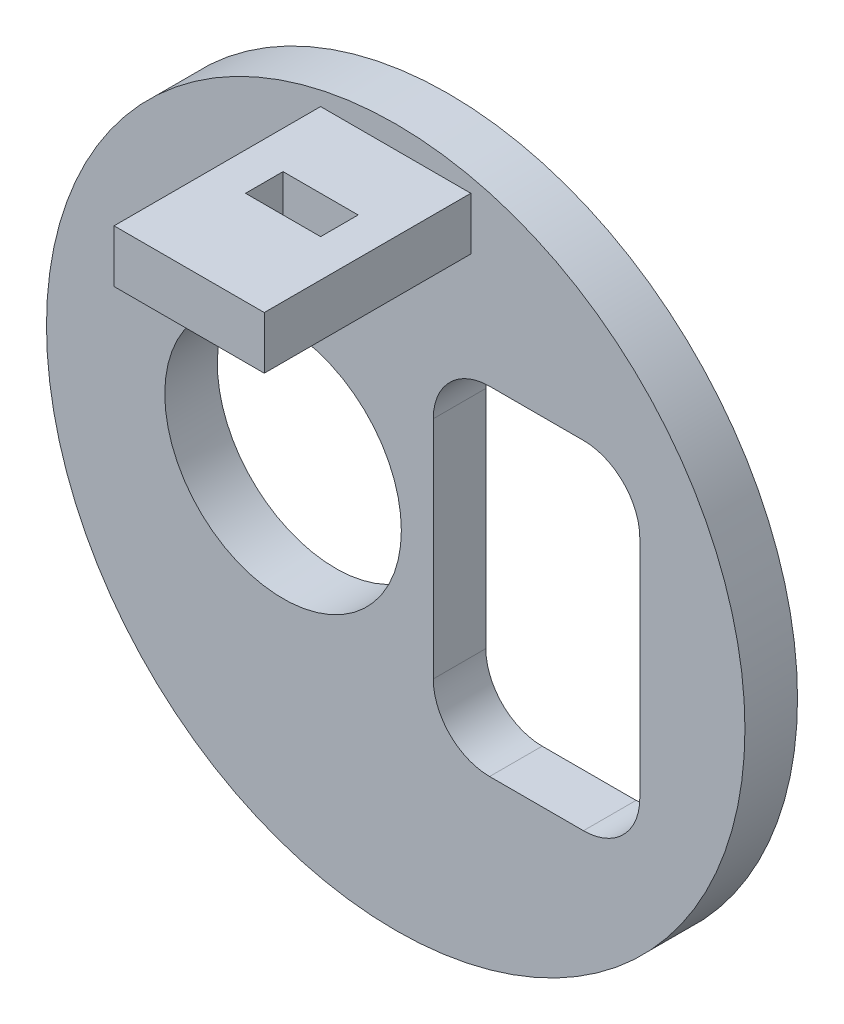
SolidWorks part; units mm, degrees
ref_plane "Front Plane" through (0, 0, 0) normal (0, 0, 1) x (1, 0, 0)
ref_plane "Top Plane" through (0, 0, 0) normal (0, 1, 0) x (1, 0, 0)
ref_plane "Right Plane" through (0, 0, 0) normal (1, 0, 0) x (0, 0, -1)
ref_plane "Plane_Z+61.8" through (0, 0, 61.8) normal (0, 0, 1) x (1, 0, 0)
sketch "Sketch1" plane through (0, 0, 61.8) normal (0, 0, 1) x (1, 0, 0)
  circle A0 centre (48, 0) radius 18.6
extrude "Cap_disc" add sketch "Sketch1" along normal blind 2.8
ref_plane "Plane_Z+64.6" through (0, 0, 64.6) normal (0, 0, 1) x (1, 0, 0)
sketch "Sketch2" plane through (0, 0, 64.6) normal (0, 0, 1) x (1, 0, 0)
  line L0 (44, 14.6) -> (52, 14.6)
  line L1 (52, 14.6) -> (52, 17.4)
  line L2 (52, 17.4) -> (44, 17.4)
  line L3 (44, 17.4) -> (44, 14.6)
extrude "Strain_relief_tab" add sketch "Sketch2" along normal blind 11
sketch "Sketch3" plane through (0, 0, 61.8) normal (0, 0, 1) x (1, 0, 0)
  circle A0 centre (42, 0) radius 6.3
  dimension "PhBore" = 12.6
extrude "pH_electrode_bore" cut sketch "Sketch3" against normal through all and the other way through all
sketch "Sketch4" plane through (0, 0, 61.8) normal (0, 0, 1) x (1, 0, 0)
  line L0 (53, -9) -> (58, -9)
  line L1 (61, -6) -> (61, 6)
  line L2 (58, 9) -> (53, 9)
  line L3 (50, 6) -> (50, -6)
  arc A0 (58, -9) -> (61, -6) centre (58, -6) ccw
  arc A1 (61, 6) -> (58, 9) centre (58, 6) ccw
  arc A2 (53, 9) -> (50, 6) centre (53, 6) ccw
  arc A3 (50, -6) -> (53, -9) centre (53, -6) ccw
extrude "Cable_and_hose_window" cut sketch "Sketch4" against normal through all and the other way through all
ref_plane "Plane_Y+13.0" through (0, 13, 0) normal (0, 1, 0) x (1, 0, 0)
sketch "Sketch5" plane through (0, 13, 0) normal (0, 1, 0) x (1, 0, 0)
  line L0 (46, -68.6) -> (50, -68.6)
  line L1 (50, -68.6) -> (50, -70.6)
  line L2 (50, -70.6) -> (46, -70.6)
  line L3 (46, -70.6) -> (46, -68.6)
extrude "Zip_tie_slot" cut sketch "Sketch5" against normal through all and the other way through all
